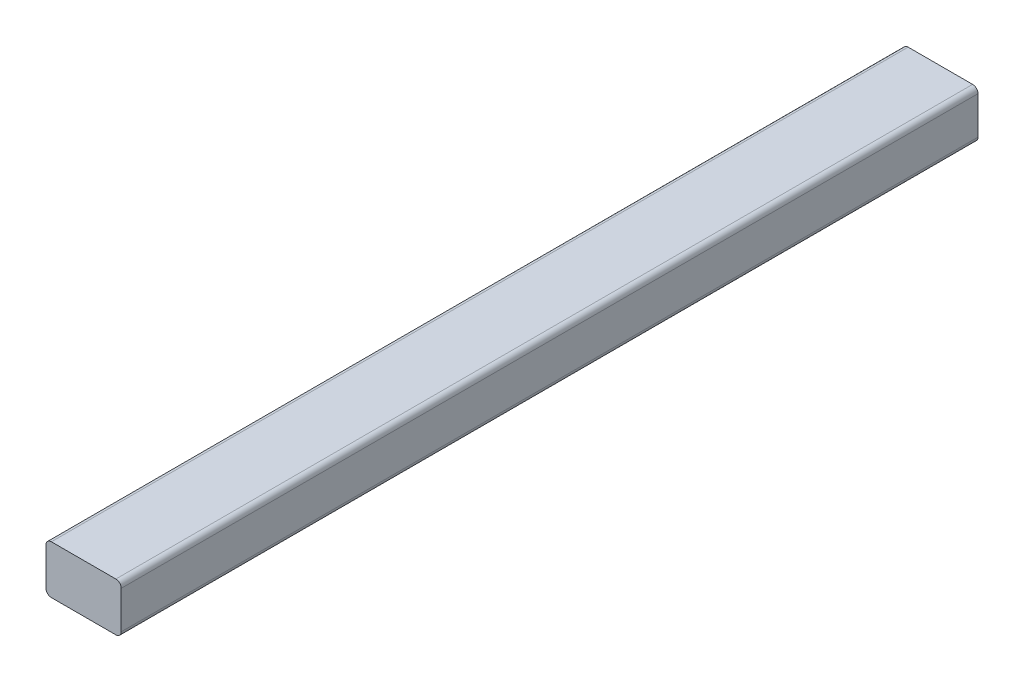
SolidWorks part; units mm, degrees
material "Beech"
ref_plane "Front Plane" through (0, 0, 0) normal (0, 0, 1) x (1, 0, 0)
ref_plane "Top Plane" through (0, 0, 0) normal (0, 1, 0) x (1, 0, 0)
ref_plane "Right Plane" through (0, 0, 0) normal (1, 0, 0) x (0, 0, -1)
sketch "Sketch1" plane through (0, 0, 0) normal (0, 0, 1) x (1, 0, 0)
  line L0 (-37.6321, 25.5658) -> (-37.6321, -9.4342)
  line L1 (-32.6321, -14.4342) -> (27.3679, -14.4342)
  line L2 (32.3679, -9.4342) -> (32.3679, 25.5658)
  line L3 (27.3679, 30.5658) -> (-32.6321, 30.5658)
  arc A0 (-37.6321, -9.4342) -> (-32.6321, -14.4342) centre (-32.6321, -9.4342) ccw
  arc A1 (27.3679, -14.4342) -> (32.3679, -9.4342) centre (27.3679, -9.4342) ccw
  arc A2 (32.3679, 25.5658) -> (27.3679, 30.5658) centre (27.3679, 25.5658) ccw
  arc A3 (-32.6321, 30.5658) -> (-37.6321, 25.5658) centre (-32.6321, 25.5658) ccw
  dimension "D1" = 5
extrude "Boss-Extrude1" add sketch "Sketch1" along normal blind 797
